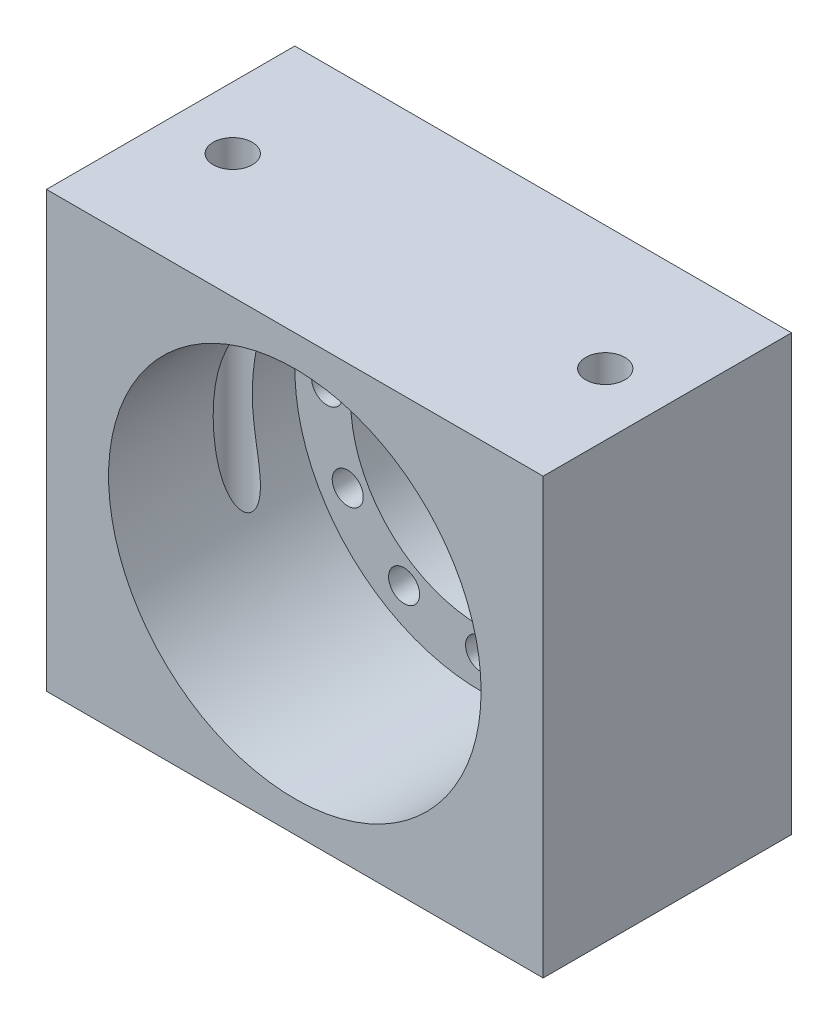
SolidWorks part; units mm, degrees
material "ABS"
ref_plane "Front Plane" through (0, 0, 0) normal (0, 0, 1) x (1, 0, 0)
ref_plane "Top Plane" through (0, 0, 0) normal (0, 1, 0) x (1, 0, 0)
ref_plane "Right Plane" through (0, 0, 0) normal (1, 0, 0) x (0, 0, -1)
sketch "Sketch1" plane through (0, 0, 0) normal (0, 0, 1) x (1, 0, 0)
  line L1 (0, 0) -> (50.8, 0)
  line L2 (0, 0) -> (0, 44.45)
  line L3 (0, 44.45) -> (50.8, 44.45)
  line L4 (50.8, 0) -> (50.8, 44.45)
  dimension "D1" = 50.8
  dimension "D2" = 44.45
extrude "Boss-Extrude1" add sketch "Sketch1" along normal blind 25.4
sketch "Sketch2" plane through (0, 0, 25.4) normal (0, 0, 1) x (1, 0, 0)
  line L0 (0, 0) -> (50.8, 0) construction
  line L1 (0, 44.45) -> (0, 0) construction
  circle A0 centre (25.4, 22.225) radius 19.05
  dimension "D1" = 38.1
  dimension "D2" = 22.225
  dimension "D3" = 25.4
extrude "Cut-Extrude1" cut sketch "Sketch2" against normal blind 19.05
sketch "Sketch3" plane through (0, 0, 6.35) normal (0, 0, 1) x (1, 0, 0)
  circle A0 centre (25.4, 22.225) radius 13.335
  circle A1 centre (25.4, 22.225) radius 19.05 construction
  circle A2 centre (9.652, 22.225) radius 1.5875
  circle A3 centre (11.7618, 30.099) radius 1.5875
  circle A4 centre (17.526, 35.8632) radius 1.5875
  circle A5 centre (25.4, 37.973) radius 1.5875
  circle A6 centre (33.274, 35.8632) radius 1.5875
  circle A7 centre (39.0382, 30.099) radius 1.5875
  circle A8 centre (41.148, 22.225) radius 1.5875
  circle A9 centre (39.0382, 14.351) radius 1.5875
  circle A10 centre (33.274, 8.5868) radius 1.5875
  circle A11 centre (25.4, 6.477) radius 1.5875
  circle A12 centre (17.526, 8.5868) radius 1.5875
  circle A13 centre (11.7618, 14.351) radius 1.5875
  point P31 (25.4, 22.225)
  dimension "D2" = 26.67
  dimension "D3" = 3.175
  dimension "D1" = 0
  dimension "D4" = 15.748
  dimension "D5" = 12
extrude "Cut-Extrude2" cut sketch "Sketch3" against normal through all
sketch "Sketch4" plane through (0, 44.45, 0) normal (0, 1, 0) x (1, 0, 0)
  line L0 (50.8, -25.4) -> (0, -25.4) construction
  line L1 (0, -25.4) -> (0, 0) construction
  circle A0 centre (6.35, -12.7) radius 2
  circle A1 centre (44.45, -12.7) radius 2
  dimension "D1" = 4
  dimension "D2" = 12.7
  dimension "D3" = 38.1
  dimension "D4" = 6.35
extrude "Cut-Extrude3" cut sketch "Sketch4" against normal through all
